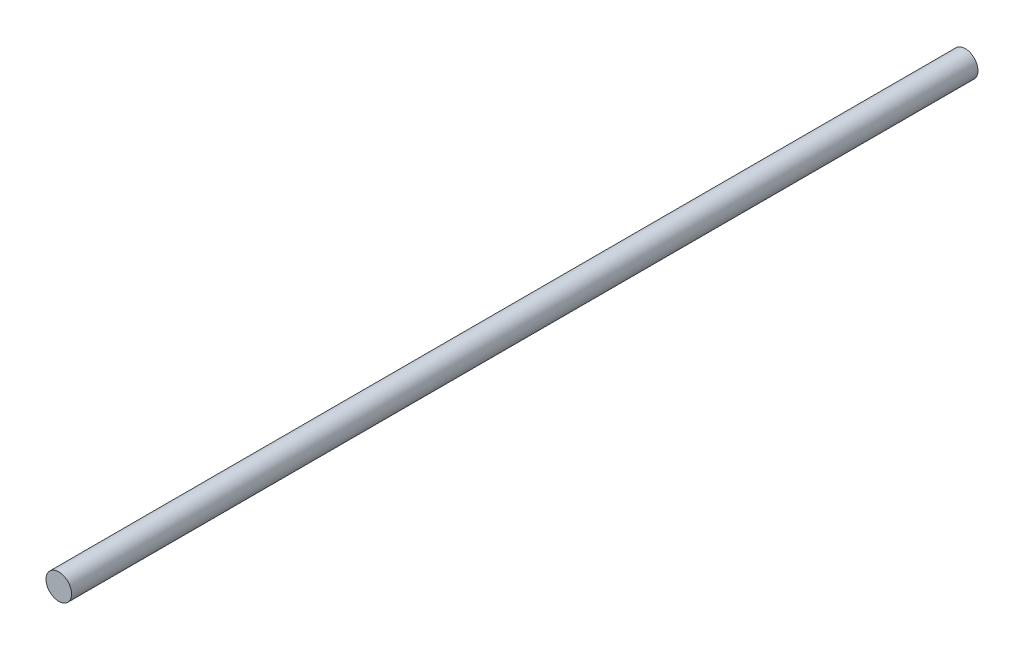
SolidWorks part; units mm, degrees
ref_plane "Płaszczyzna przednia" through (0, 0, 0) normal (0, 0, 1) x (1, 0, 0)
ref_plane "Płaszczyzna górna" through (0, 0, 0) normal (0, 1, 0) x (1, 0, 0)
ref_plane "Płaszczyzna prawa" through (0, 0, 0) normal (1, 0, 0) x (0, 0, -1)
sketch "Szkic1" plane through (0, 0, 0) normal (0, 0, 1) x (1, 0, 0)
  circle A0 centre (0, 0) radius 12.5
  dimension "D1" = 25
extrude "Dodanie-wyciągnięcie1" add sketch "Szkic1" along normal blind 885
